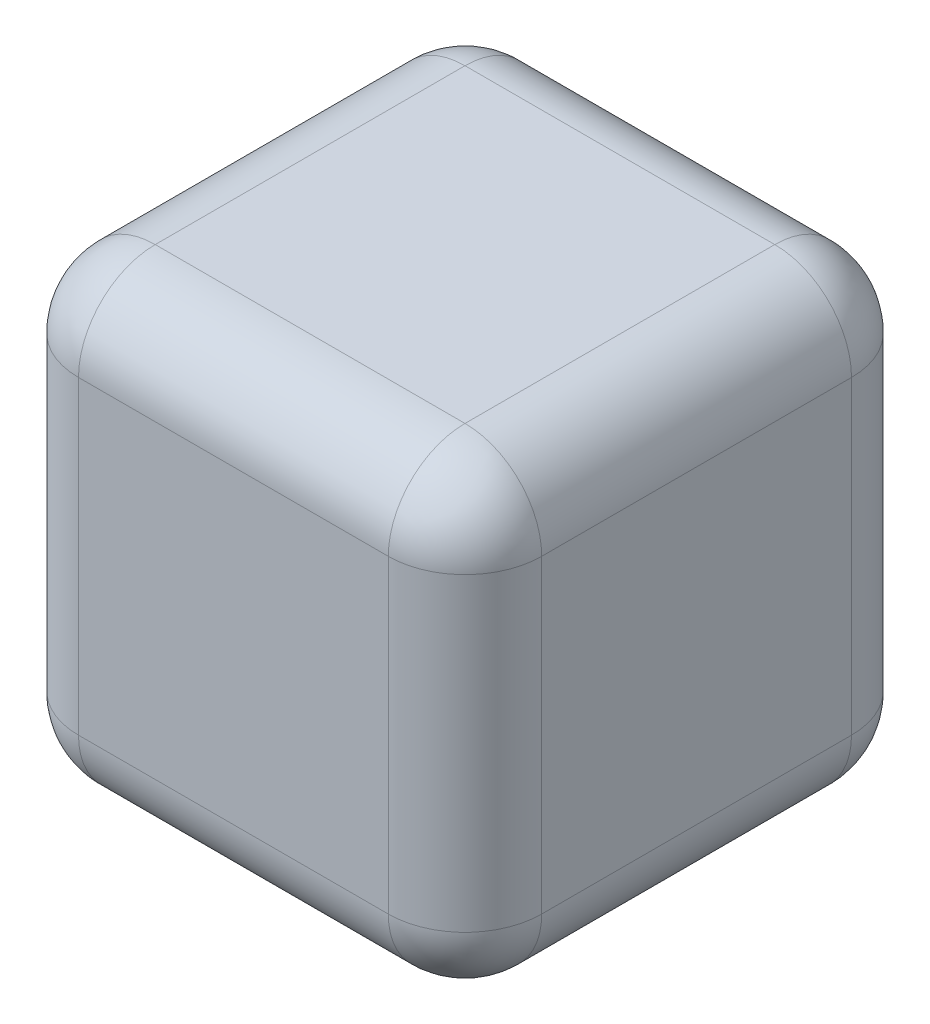
SolidWorks part; units mm, degrees
ref_plane "Front Plane" through (0, 0, 0) normal (0, 0, 1) x (1, 0, 0)
ref_plane "Top Plane" through (0, 0, 0) normal (0, 1, 0) x (1, 0, 0)
ref_plane "Right Plane" through (0, 0, 0) normal (1, 0, 0) x (0, 0, -1)
sketch "Sketch1" plane through (0, 0, 0) normal (0, 0, 1) x (1, 0, 0)
  line L1 (-32, -32) -> (32, -32)
  line L2 (-32, -32) -> (-32, 32)
  line L3 (-32, 32) -> (32, 32)
  line L4 (32, -32) -> (32, 32)
  line L5 (-32, -32) -> (32, 32) construction
  line L6 (-32, 32) -> (32, -32) construction
  point P0 (0, 0)
  dimension "D1" = 64
extrude "Boss-Extrude1" add sketch "Sketch1" along normal blind 64
fillet "Fillet1" radius 10.6 12 edges at (-32, -32, 32) (-32, 32, 32) (0, -32, 64) (-32, 0, 64) (0, 32, 64) (0, 32, 0) (-32, 0, 0) (0, -32, 0) (32, -32, 32) (32, 0, 64) (32, 32, 32) (32, 0, 0)
